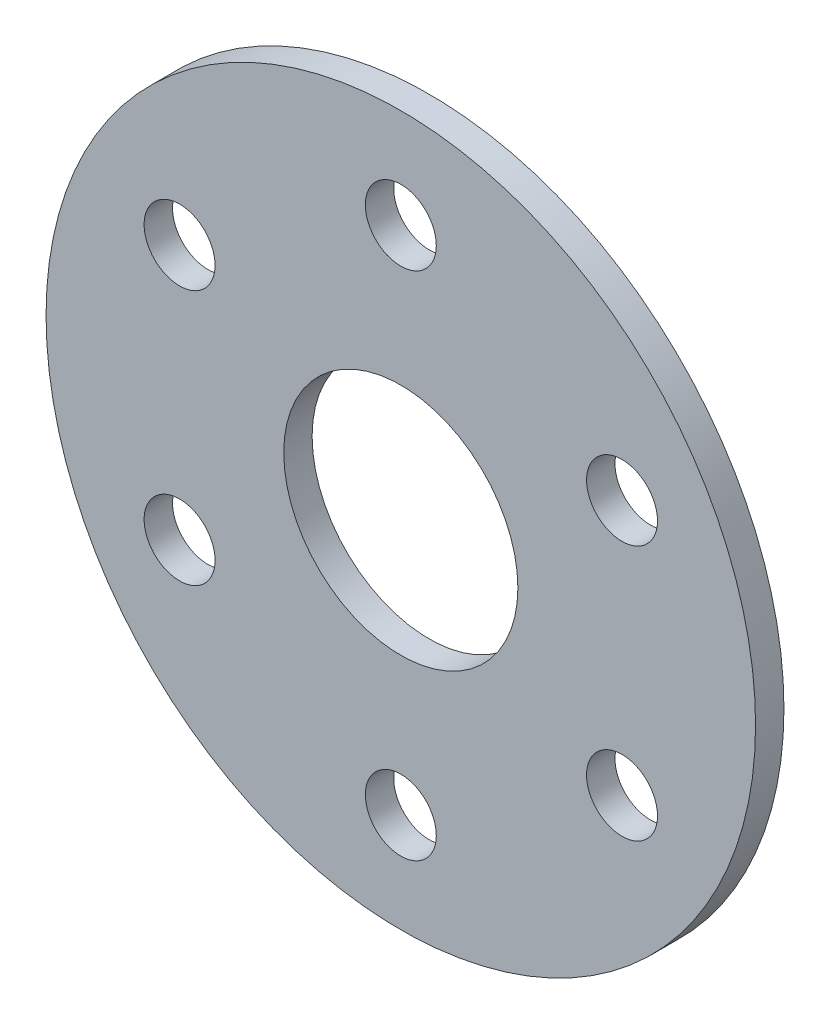
SolidWorks part; units mm, degrees
ref_plane "Front Plane" through (0, 0, 0) normal (0, 0, 1) x (1, 0, 0)
ref_plane "Top Plane" through (0, 0, 0) normal (0, 1, 0) x (1, 0, 0)
ref_plane "Right Plane" through (0, 0, 0) normal (1, 0, 0) x (0, 0, -1)
sketch "Sketch1" plane through (0, 0, 0) normal (0, 0, 1) x (1, 0, 0)
  line L0 (0, 0) -> (0, 26.9239) construction
  line L1 (0, 0) -> (37.0605, 0) construction
  circle A0 centre (0, 0) radius 8.25
  circle A1 centre (0, 0) radius 18 construction
  circle A2 centre (0, 0) radius 25
  circle A3 centre (0, 18) radius 2.5
  circle A4 centre (15.5885, 9) radius 2.5
  circle A5 centre (15.5885, -9) radius 2.5
  circle A6 centre (0, -18) radius 2.5
  circle A7 centre (-15.5885, -9) radius 2.5
  circle A8 centre (-15.5885, 9) radius 2.5
  point P22 (0, 0)
  dimension "D1" = 50
  dimension "D2" = 16.5
  dimension "D3" = 36
  dimension "D4" = 5
  dimension "D5" = 6
extrude "Boss-Extrude1" add sketch "Sketch1" along normal mid plane 2
